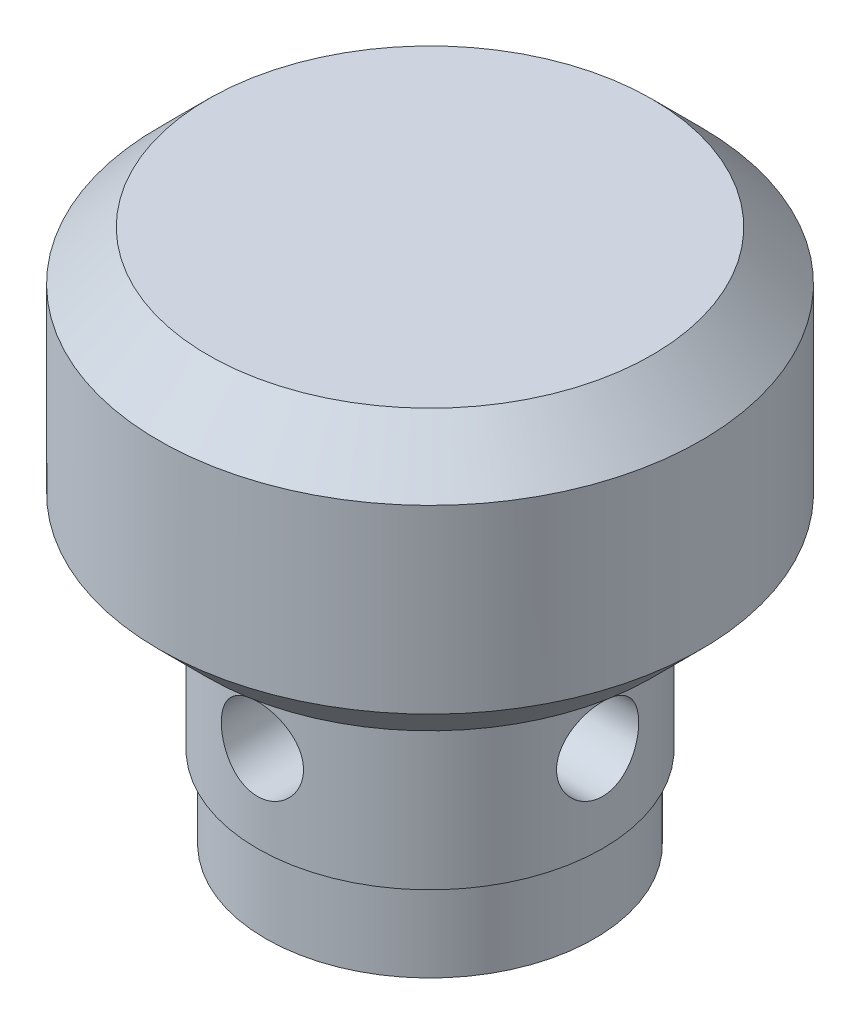
SolidWorks part; units mm, degrees
ref_plane "Front" through (0, 0, 0) normal (0, 0, 1) x (1, 0, 0)
ref_plane "Top" through (0, 0, 0) normal (0, 1, 0) x (1, 0, 0)
ref_plane "Right" through (0, 0, 0) normal (1, 0, 0) x (0, 0, -1)
sketch "Sketch1" plane through (0, 0, 0) normal (0, 1, 0) x (1, 0, 0)
  line L0 (-9.3927, 12.4091) -> (-9.3927, -8.5909)
  line L1 (-9.3927, -8.5909) -> (11.6073, -8.5909)
  line L2 (11.6073, -8.5909) -> (11.6073, 12.4091)
  line L3 (11.6073, 12.4091) -> (-9.3927, 12.4091)
  dimension "D1" = 21
  dimension "D2" = 21
extrude "Boss-Extrude1" add sketch "Sketch1" along normal blind 10.5
sketch "Sketch2" plane through (0, 0, 8.5909) normal (0, 0, 1) x (1, 0, 0)
  line L0 (1.1073, 10.5) -> (1.1073, 0)
  line L1 (-9.3927, 10.5) -> (11.6073, 10.5) construction
  line L2 (-9.3927, 0) -> (11.6073, 0) construction
  circle A0 centre (1.1073, 5.25) radius 2.5
  dimension "D1" = 5
extrude "Cut-Extrude1" cut sketch "Sketch2" against normal blind 24.5 contours L0 A0 | L0 A0
sketch "Sketch3" plane through (-9.3927, 0, 0) normal (-1, 0, 0) x (0, 0, 1)
  line L0 (-1.9091, 10.5) -> (-1.9091, 0)
  line L1 (-12.4091, 10.5) -> (8.5909, 10.5) construction
  line L2 (-12.4091, 0) -> (8.5909, 0) construction
  circle A0 centre (-1.9091, 5.25) radius 2.5
  dimension "D1" = 5
extrude "Cut-Extrude2" cut sketch "Sketch3" against normal blind 24.5 contours L0 A0 | L0 A0
sketch "Sketch4" plane through (0, 10.5, 0) normal (0, 1, 0) x (1, 0, 0)
  line L0 (1.1073, 12.4091) -> (1.1073, -8.5909)
  line L1 (11.6073, 12.4091) -> (-9.3927, 12.4091) construction
  line L2 (-9.3927, -8.5909) -> (11.6073, -8.5909) construction
  line L3 (-9.3927, 12.4091) -> (-9.3927, -8.5909)
  line L4 (-9.3927, -8.5909) -> (11.6073, -8.5909)
  line L5 (11.6073, -8.5909) -> (11.6073, 12.4091)
  line L6 (11.6073, 12.4091) -> (-9.3927, 12.4091)
  circle A0 centre (1.1073, 1.9091) radius 10.5
  line M6 (11.6073, 12.4091) -> (-9.3927, 12.4091)
  line M7 (-9.3927, 12.4091) -> (-9.3927, -8.5909)
  line M8 (-9.3927, -8.5909) -> (11.6073, -8.5909)
  line M9 (11.6073, -8.5909) -> (11.6073, 12.4091)
  dimension "D1" = 21
extrude "Cut-Extrude3" cut sketch "Sketch4" against normal blind 24.5 contours A0 M6 M7 | A0 L5 M6 | A0 M8 M9 | A0 L3 M8
sketch "Sketch5" plane through (0, 10.5, 0) normal (0, 1, 0) x (1, 0, 0)
  circle A0 centre (1.1073, 1.9091) radius 16.5
  dimension "D1" = 33
extrude "Boss-Extrude2" add sketch "Sketch5" along normal blind 17
chamfer "Chamfer4" distance 3 angle 45 1 edges at (1.1073, 27.5, 14.5909)
chamfer "Chamfer5" distance 3 angle 45 1 edges at (1.1073, 10.5, 14.5909)
sketch "Sketch6" plane through (0, 0, 0) normal (0, -1, 0) x (1, 0, 0)
  circle A0 centre (1.1073, -1.9091) radius 10.5
sketch "Sketch13" plane through (0, 0, 0) normal (0, -1, 0) x (1, 0, 0)
  circle A0 centre (1.1073, -1.9091) radius 10
  dimension "D1" = 20
extrude "Boss-Extrude6" add sketch "Sketch13" along normal blind 5
cosmetic thread "Rosca cosmética1" parameters "D2"=18.344
sketch "Sketch14" plane through (0, -5, 0) normal (0, -1, 0) x (1, 0, 0)
  circle A0 centre (1.1073, -1.9091) radius 2.5
  dimension "D1" = 5
extrude "Cut-Extrude7" cut sketch "Sketch14" against normal blind 10
